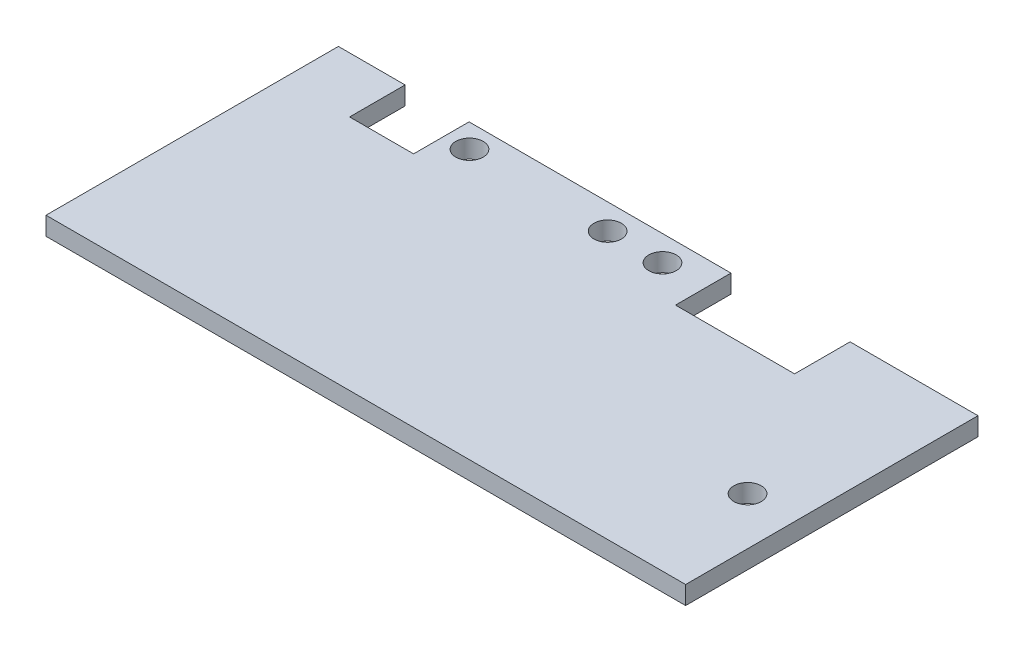
SolidWorks part; units mm, degrees
material "Silicon"
ref_plane "Front Plane" through (0, 0, 0) normal (0, 0, 1) x (1, 0, 0)
ref_plane "Top Plane" through (0, 0, 0) normal (0, 1, 0) x (1, 0, 0)
ref_plane "Right Plane" through (0, 0, 0) normal (1, 0, 0) x (0, 0, -1)
sketch "Sketch1" plane through (0, 0, 0) normal (0, 1, 0) x (1, 0, 0)
  line L0 (0, 0) -> (0, 16)
  line L1 (0, 16) -> (3.65, 16)
  line L2 (3.65, 16) -> (3.65, 12.964)
  line L3 (3.65, 12.964) -> (7.15, 12.964)
  line L4 (7.15, 12.964) -> (7.15, 16)
  line L5 (7.15, 16) -> (21.483, 16)
  line L6 (21.483, 16) -> (21.483, 12.964)
  line L7 (21.483, 12.964) -> (28, 12.964)
  line L8 (28, 12.964) -> (28, 16)
  line L9 (28, 16) -> (35, 16)
  line L10 (35, 16) -> (35, 0)
  line L11 (35, 0) -> (0, 0)
  dimension "D1" = 35
  dimension "D2" = 16
  dimension "D3" = 16
  dimension "D4" = 3.036
  dimension "D5" = 3.036
  dimension "D6" = 3.036
  dimension "D7" = 3.65
  dimension "D8" = 14.333
  dimension "D9" = 7
  dimension "D10" = 3.5
extrude "Boss-Extrude1" add sketch "Sketch1" along normal blind 1
sketch "Sketch3" plane through (0, 1, 0) normal (0, 1, 0) x (1, 0, 0)
  line L0 (0, 0) -> (35, 0) construction
  line L1 (35, 0) -> (35, 16) construction
  circle A0 centre (32.39, 6) radius 0.75
  dimension "D1" = 1.5
  dimension "D2" = 6
  dimension "D3" = 2.61
extrude "Cut-Extrude2" cut sketch "Sketch3" against normal through all
sketch "Sketch4" plane through (0, 1, 0) normal (0, 1, 0) x (1, 0, 0)
  circle A0 centre (8.46, 14.713) radius 0.75
  circle A1 centre (16.121, 14.613) radius 0.75
  circle A2 centre (19.121, 14.613) radius 0.75
extrude "Cut-Extrude3" cut sketch "Sketch4" against normal through all both
